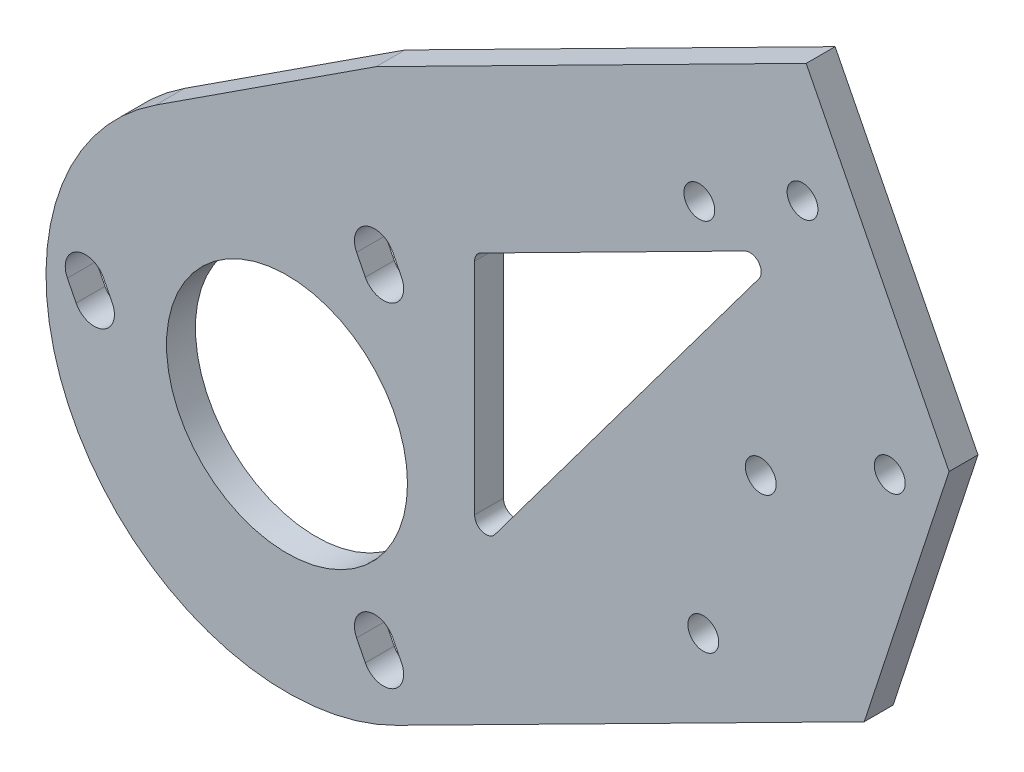
SolidWorks part; units mm, degrees
material "Thornel Mat VMA"
ref_plane "Front Plane" through (0, 0, 0) normal (0, 0, 1) x (1, 0, 0)
ref_plane "Top Plane" through (0, 0, 0) normal (0, 1, 0) x (1, 0, 0)
ref_plane "Right Plane" through (0, 0, 0) normal (1, 0, 0) x (0, 0, -1)
sketch "Sketch1" plane through (0, 0, 0) normal (0, 0, 1) x (1, 0, 0)
  line L0 (90.0105, -12.9175) -> (53.8576, 58.4475) construction
  line L1 (53.8576, 58.4475) -> (-8.5868, 26.8137) construction
  line L2 (77.7186, 11.3466) -> (53.8576, 58.4475)
  line L3 (53.8576, 58.4475) -> (9.2545, 35.852)
  line L4 (-13.6372, 20.953) -> (9.2545, 35.852)
  line L5 (11.2978, -22.3016) -> (77.7186, 11.3466)
  line L6 (10, 17.3205) -> (9.0962, 19.1046) construction
  line L7 (8.1267, 16.3715) -> (7.2228, 18.1556)
  line L8 (11.8733, 18.2695) -> (10.9695, 20.0536)
  line L9 (-20, 0) -> (-20.9038, 1.7841) construction
  line L10 (-21.8733, -0.949) -> (-22.7772, 0.8351)
  line L11 (-18.1267, 0.949) -> (-19.0305, 2.7331)
  line L12 (10, -17.3205) -> (9.0962, -15.5364) construction
  line L13 (8.1267, -18.2695) -> (7.2228, -16.4854)
  line L14 (11.8733, -16.3715) -> (10.9695, -14.5874)
  arc A0 (-13.6372, 20.953) -> (11.2978, -22.3016) centre (0, 0) ccw
  arc A1 (24.6073, -24.6073) -> (-24.6073, 24.6073) centre (0, 0) ccw construction
  circle A2 centre (0, 0) radius 12.5
  arc A3 (8.1267, 16.3715) -> (11.8733, 18.2695) centre (10, 17.3205) ccw
  arc A4 (10.9695, 20.0536) -> (7.2228, 18.1556) centre (9.0962, 19.1046) ccw
  arc A5 (-21.8733, -0.949) -> (-18.1267, 0.949) centre (-20, 0) ccw
  arc A6 (-19.0305, 2.7331) -> (-22.7772, 0.8351) centre (-20.9038, 1.7841) ccw
  arc A7 (8.1267, -18.2695) -> (11.8733, -16.3715) centre (10, -17.3205) ccw
  arc A8 (10.9695, -14.5874) -> (7.2228, -16.4854) centre (9.0962, -15.5364) ccw
  circle A9 centre (53.4763, 45.9234) radius 1.6 construction
  circle A10 centre (42.7715, 40.5004) radius 1.6 construction
  circle A11 centre (53.4763, 45.9234) radius 1.6
  circle A12 centre (42.7715, 40.5004) radius 1.6
  point P16 (9.5481, 18.2126)
  point P21 (-20.4519, 0.8921)
  point P29 (9.5481, -16.4284)
  dimension "D1" = 50
  dimension "D3" = 25
  dimension "D4" = 2.1
  dimension "D2" = 50
  dimension "D5" = 2
extrude "Extrude1" add sketch "Sketch1" along normal blind 3
chamfer "Chamfer1" distance 20 angle 45 1 edges at (77.7186, 11.3466, 1.5)
sketch "Sketch2" plane through (0, 0, 3) normal (0, 0, 1) x (1, 0, 0)
  line L0 (49.1453, 19.0674) -> (68.7707, 29.0095) construction
  line L1 (68.6803, 29.1879) -> (53.8576, 58.4475) construction
  line L2 (-8.5868, 26.8137) -> (53.8576, 58.4475) construction
  circle A0 centre (62.5263, 25.8461) radius 1.6
  circle A1 centre (49.1453, 19.0674) radius 1.6
  circle A2 centre (43.188, 1.8993) radius 1.6
  point P4 (38.5211, 11.1334)
  point P12 (43.188, 1.8993)
  dimension "D1" = 3.2
  dimension "D2" = 7
  dimension "D3" = 15
  dimension "D5" = 3.2
  dimension "D4" = 33
extrude "Cut-Extrude1" cut sketch "Sketch2" against normal blind 3
sketch "Sketch4" plane through (0, 0, 3) normal (0, 0, 1) x (1, 0, 0)
  line L0 (20.1023, 24.5324) -> (47.4889, 38.4062)
  line L1 (48.9603, 36.6562) -> (21.5738, -0.0179)
  line L2 (19.4588, 0.6847) -> (19.4588, 23.485)
  line L8 (53.8576, 58.4475) -> (9.2545, 35.852) construction
  arc A3 (21.5738, -0.0179) -> (19.4588, 0.6847) centre (20.633, 0.6847) cw
  arc A4 (47.4889, 38.4062) -> (48.9603, 36.6562) centre (48.0195, 37.3588) cw
  arc A5 (20.1023, 24.5324) -> (19.4588, 23.485) centre (20.633, 23.485) ccw
  point P2 (48.0195, 37.3588)
  point P6 (60.9797, 24.1032)
  point P7 (20.4622, -5.9162)
  point P12 (37.3126, -3.5177)
  point P13 (28.7266, -7.8673)
  point P28 (21.552, 33.0949)
  point P29 (39.7533, 33.5887)
  point P30 (21.9622, 3.2684)
  point P33 (36.4681, 33.05)
  point P34 (0, 0)
  point P35 (47.4871, 36.4618)
  point P38 (18.6375, -0.581)
  point P39 (0, 0)
  point P40 (47.7006, 36.832)
  dimension "D6" = 15
extrude "Cut-Extrude3" cut sketch "Sketch4" against normal blind 3
